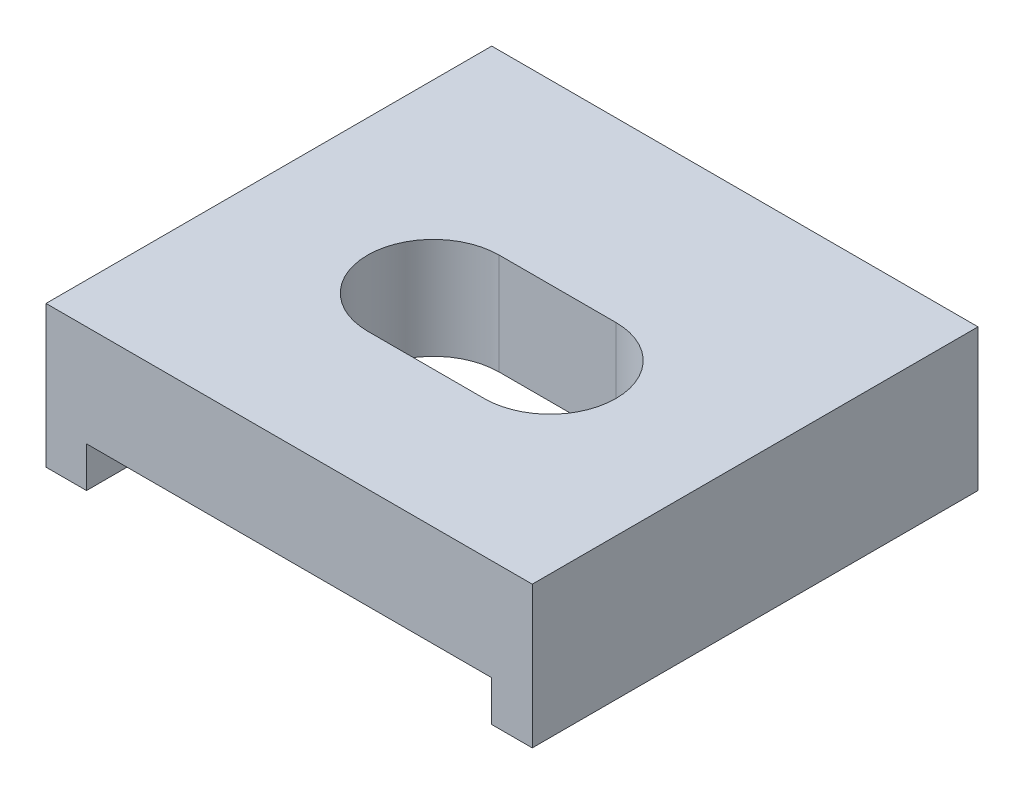
SolidWorks part; units mm, degrees
ref_plane "Front Plane" through (0, 0, 0) normal (0, 0, 1) x (1, 0, 0)
ref_plane "Top Plane" through (0, 0, 0) normal (0, 1, 0) x (1, 0, 0)
ref_plane "Right Plane" through (0, 0, 0) normal (1, 0, 0) x (0, 0, -1)
sketch "Sketch1" plane through (0, 0, 0) normal (0, 1, 0) x (1, 0, 0)
  line L0 (-5, -5) -> (5, -5)
  line L1 (-5, -5) -> (-5, 5)
  line L2 (5, -5) -> (5, 5)
  line L3 (-5, 5) -> (5, 5)
  line L4 (0, -5) -> (0, 5) construction
  line L6 (-5, 0) -> (5, 0) construction
  line L9 (1.44, 0) -> (-1.44, 0) construction
  line L10 (1.44, -1.625) -> (-1.44, -1.625)
  line L11 (1.44, 1.625) -> (-1.44, 1.625)
  circle A0 centre (-1.75, 0) radius 0.31
  circle A1 centre (0, 0) radius 0.62
  circle A2 centre (1.75, 0) radius 0.31
  arc A5 (1.44, -1.625) -> (1.44, 1.625) centre (1.44, 0) ccw
  arc A6 (-1.44, 1.625) -> (-1.44, -1.625) centre (-1.44, 0) ccw
  point P24 (0, 0)
  dimension "D5" = 0.62
  dimension "D9" = 1.24
  dimension "D10" = 0.62
  dimension "D2" = 10
  dimension "D3" = 1.75
  dimension "D4" = 1.75
  dimension "D7" = 10
extrude "Boss-Extrude1" add sketch "Sketch1" along normal blind 2.5 contours L3 L1 L0 L2 A6 L11 A5 L10
sketch "Sketch2" plane through (0, 2.5, 0) normal (0, 1, 0) x (1, 0, 0)
  line L0 (-5, -5) -> (-5, 5)
  line L1 (5, -5) -> (6, -5)
  line L2 (-5, -5) -> (-5, 5) construction
  line L3 (-5, 5) -> (5, 5) construction
  line L4 (-5, 5) -> (5, 5)
  line L5 (-5, -5) -> (-6, -5)
  line L6 (5, 5) -> (5, -5)
  line L7 (6, -5) -> (6, 6)
  line L8 (-6, 6) -> (-6, -5)
  line L11 (-6, 6) -> (6, 6)
extrude "Boss-Extrude2" add sketch "Sketch2" against normal blind 3.5 contours L8 L5 L0 L4 L6 L1 L7 L11
